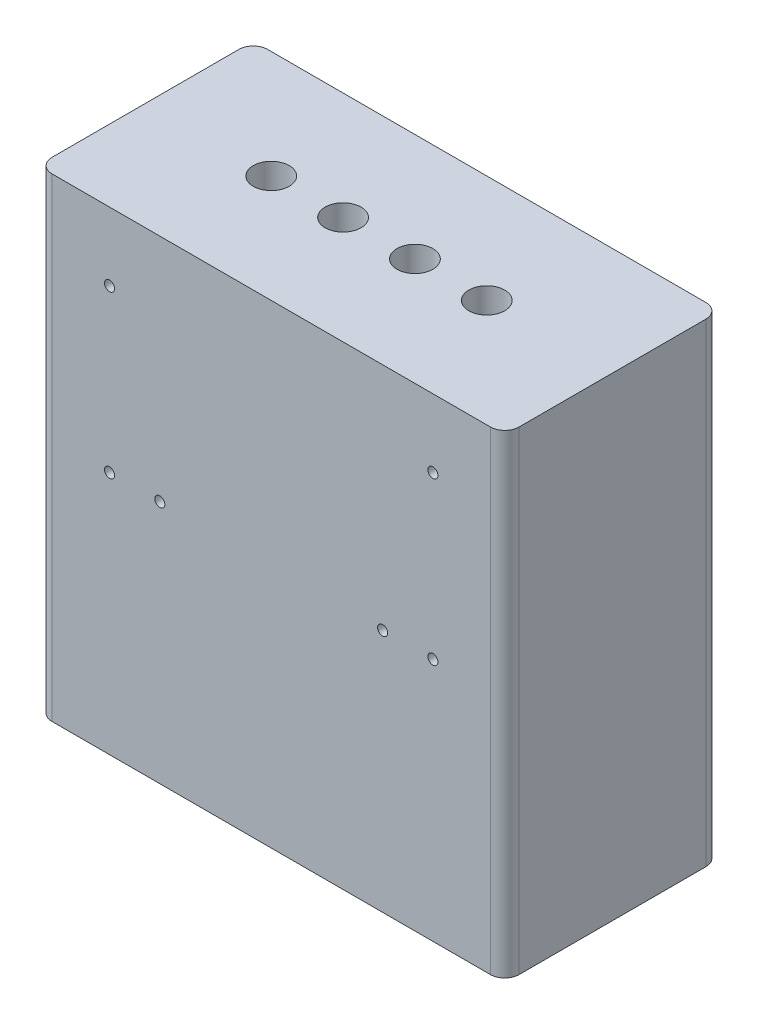
SolidWorks part; units mm, degrees
material "Mahogany"
ref_plane "Front Plane" through (0, 0, 0) normal (0, 0, 1) x (1, 0, 0)
ref_plane "Top Plane" through (0, 0, 0) normal (0, 1, 0) x (1, 0, 0)
ref_plane "Right Plane" through (0, 0, 0) normal (1, 0, 0) x (0, 0, -1)
sketch "Sketch1" plane through (0, 0, 0) normal (0, 0, 1) x (1, 0, 0)
  line L1 (-41.275, -41.91) -> (41.275, -41.91)
  line L2 (-41.275, -41.91) -> (-41.275, 41.91)
  line L3 (-41.275, 41.91) -> (41.275, 41.91)
  line L4 (41.275, -41.91) -> (41.275, 41.91)
  line L5 (-41.275, -41.91) -> (41.275, 41.91) construction
  line L6 (-41.275, 41.91) -> (41.275, -41.91) construction
  point P0 (0, 0)
  dimension "D1" = 82.55
  dimension "D2" = 83.82
extrude "Boss-Extrude1" add sketch "Sketch1" along normal mid plane 38.1
sketch "Sketch2" plane through (0, 0, 19.05) normal (0, 0, 1) x (1, 0, 0)
  line L0 (41.275, -41.91) -> (41.275, 41.91) construction
  line L1 (-28.575, 1.27) -> (28.575, 1.27) construction
  line L2 (-28.575, 1.27) -> (-28.575, 29.845) construction
  line L3 (-28.575, 29.845) -> (28.575, 29.845) construction
  line L4 (28.575, 1.27) -> (28.575, 29.845) construction
  line L5 (-28.575, 1.27) -> (28.575, 29.845) construction
  line L6 (-28.575, 29.845) -> (28.575, 1.27) construction
  line L7 (41.275, 41.91) -> (-41.275, 41.91) construction
  circle A0 centre (-28.575, 29.845) radius 0.889
  circle A1 centre (28.575, 29.845) radius 0.889
  circle A2 centre (28.575, 1.27) radius 0.889
  circle A3 centre (-28.575, 1.27) radius 0.889
  circle A4 centre (-19.685, 1.27) radius 0.889
  circle A5 centre (19.685, 1.27) radius 0.889
  point P10 (0, 15.5575)
  dimension "D1" = 1.778
  dimension "D2" = 12.7
  dimension "D3" = 12.065
  dimension "D4" = 40.64
  dimension "D5" = 8.89
  dimension "D6" = 8.89
extrude "Cut-Extrude1" cut sketch "Sketch2" against normal through all
fillet "Fillet1" radius 2.54 4 edges at (-41.275, 0, -19.05) (41.275, 0, -19.05) (41.275, 0, 19.05) (-41.275, 0, 19.05)
sketch "Sketch3" plane through (0, 41.91, 0) normal (0, 1, 0) x (1, 0, 0)
  line L0 (-6.35, 0) -> (6.35, 0) construction
  circle A0 centre (-6.35, 0) radius 3.175
  circle A1 centre (6.35, 0) radius 3.175
  circle A2 centre (19.05, 0) radius 3.175
  circle A3 centre (-19.05, 0) radius 3.175
  dimension "D1" = 6.35
  dimension "D2" = 12.7
  dimension "D3" = 12.7
  dimension "D4" = 12.7
extrude "Cut-Extrude2" cut sketch "Sketch3" against normal blind 38.1
